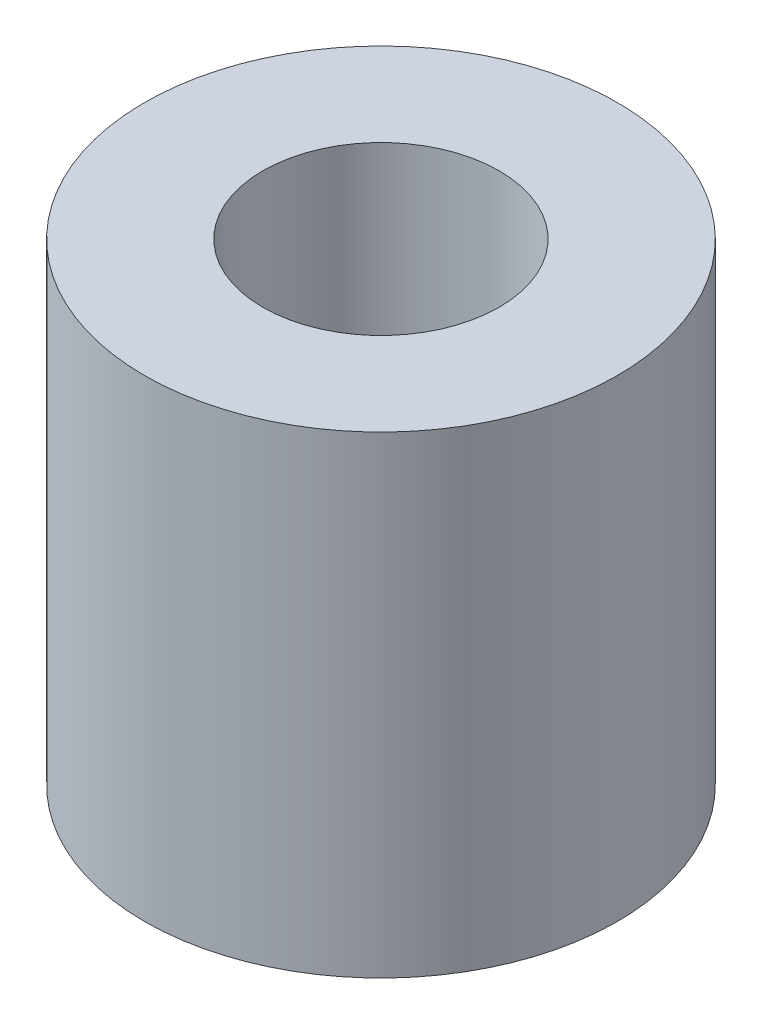
SolidWorks part; units mm, degrees
ref_plane "Спереди" through (0, 0, 0) normal (0, 0, 1) x (1, 0, 0)
ref_plane "Сверху" through (0, 0, 0) normal (0, 1, 0) x (1, 0, 0)
ref_plane "Справа" through (0, 0, 0) normal (1, 0, 0) x (0, 0, -1)
sketch "Эскиз1" plane through (0, 0, 0) normal (0, 1, 0) x (1, 0, 0)
  circle A0 centre (0, 0) radius 1.75
  circle A1 centre (0, 0) radius 3.5
  dimension "D1" = 3.5
  dimension "D2" = 7
extrude "Бобышка-Вытянуть1" add sketch "Эскиз1" along normal blind 7
